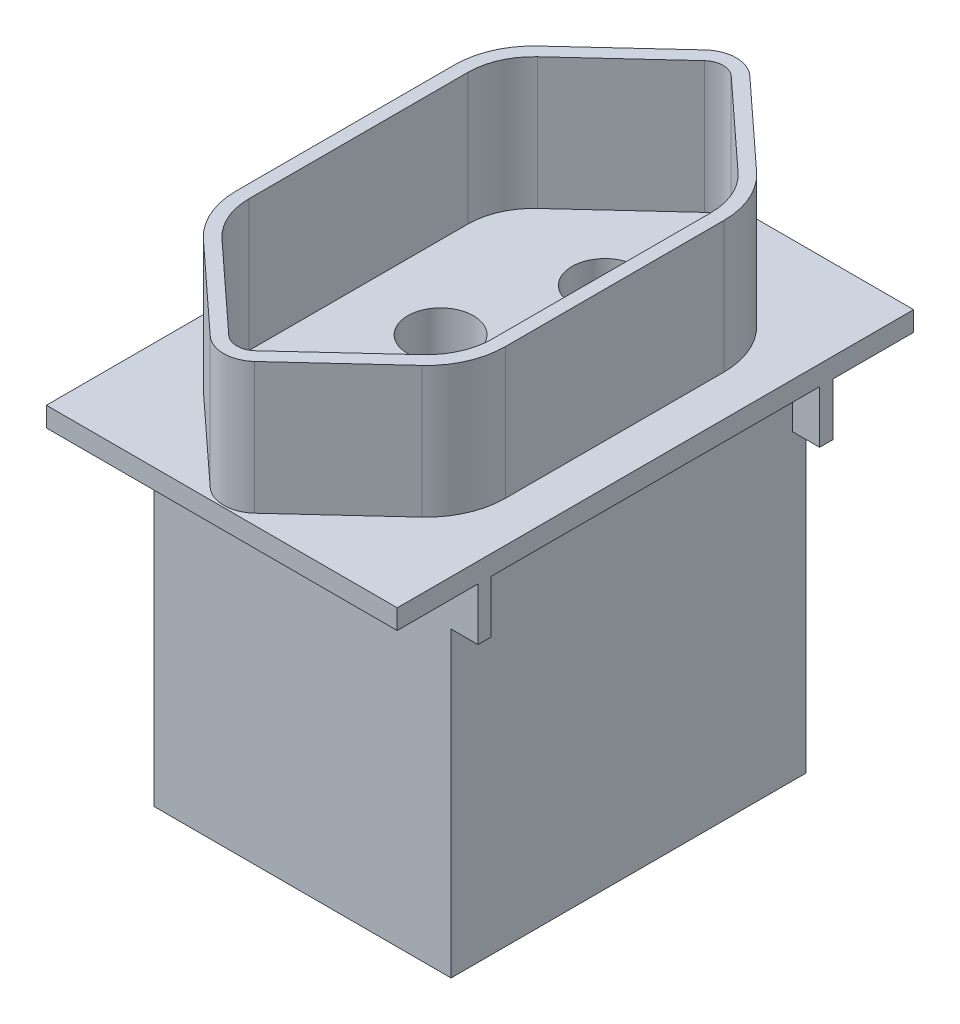
SolidWorks part; units mm, degrees
ref_plane "Plano frontal" through (0, 0, 0) normal (0, 0, 1) x (1, 0, 0)
ref_plane "Plano superior" through (0, 0, 0) normal (0, 1, 0) x (1, 0, 0)
ref_plane "Plano direito" through (0, 0, 0) normal (1, 0, 0) x (0, 0, -1)
sketch "Esboço1" plane through (0, 0, 0) normal (0, 1, 0) x (1, 0, 0)
  line L1 (-13.35, 19.65) -> (13.35, 19.65)
  line L2 (-13.35, 19.65) -> (-13.35, -19.65)
  line L3 (-13.35, -19.65) -> (13.35, -19.65)
  line L4 (13.35, 19.65) -> (13.35, -19.65)
  line L5 (-13.35, 19.65) -> (13.35, -19.65) construction
  line L6 (-13.35, -19.65) -> (13.35, 19.65) construction
  point P0 (0, 0)
  dimension "D1" = 26.7
  dimension "D2" = 39.3
extrude "Ressalto-extrusão1" add sketch "Esboço1" against normal blind 38.5
sketch "Esboço2" plane through (0, 0, 0) normal (0, 1, 0) x (1, 0, 0)
  line L0 (0, -19.04) -> (0, 19.04) construction
  line L1 (1.0166, -18.1029) -> (7.6387, -11.9991)
  line L2 (9.25, -8.3226) -> (9.25, 8.3226)
  line L3 (7.6387, 11.9991) -> (1.0166, 18.1029)
  line L4 (0, 0) -> (9.25, 0) construction
  line L5 (-1.0166, -18.1029) -> (-7.6387, -11.9991)
  line L6 (-7.6387, 11.9991) -> (-1.0166, 18.1029)
  line L7 (-9.25, -8.3226) -> (-9.25, 8.3226)
  arc A0 (9.25, 8.3226) -> (7.6387, 11.9991) centre (4.25, 8.3226) ccw
  arc A1 (7.6387, -11.9991) -> (9.25, -8.3226) centre (4.25, -8.3226) ccw
  arc A2 (-7.6387, -11.9991) -> (-9.25, -8.3226) centre (-4.25, -8.3226) cw
  arc A3 (-9.25, 8.3226) -> (-7.6387, 11.9991) centre (-4.25, 8.3226) cw
  arc A4 (1.0166, 18.1029) -> (-1.0166, 18.1029) centre (0, 17) ccw
  arc A5 (1.0166, -18.1029) -> (-1.0166, -18.1029) centre (0, -17) cw
  point P3 (0, 0)
  point P8 (6.3134, -8.4178)
  dimension "D1" = 5
  dimension "D2" = 1.5
  dimension "D3" = 37
  dimension "D4" = 28
  dimension "D5" = 18.5
extrude "Corte-extrusão1" cut sketch "Esboço2" against normal blind 10 contours A5 L1 A1 L2 A0 L3 A4 L6 A3 L7 A2 L5
sketch "Esboço4" plane through (0, 0, 0) normal (0, 1, 0) x (1, 0, 0)
  line L14 (-8.3165, -12.7344) -> (-1.6944, -18.8382)
  line L15 (1.6944, -18.8382) -> (8.3165, -12.7344)
  line L16 (10.25, -8.3226) -> (10.25, 8.3226)
  line L17 (8.3165, 12.7344) -> (1.6944, 18.8382)
  line L18 (-1.6944, 18.8382) -> (-8.3165, 12.7344)
  line L19 (-10.25, 8.3226) -> (-10.25, -8.3226)
  line L20 (1.0166, -18.1029) -> (7.6387, -11.9991)
  line L21 (9.25, -8.3226) -> (9.25, 8.3226)
  line L22 (7.6387, 11.9991) -> (1.0166, 18.1029)
  line L23 (-1.0166, 18.1029) -> (-7.6387, 11.9991)
  line L24 (-9.25, 8.3226) -> (-9.25, -8.3226)
  line L25 (-7.6387, -11.9991) -> (-1.0166, -18.1029)
  line L26 (1.0166, -18.1029) -> (7.6387, -11.9991)
  line L27 (9.25, -8.3226) -> (9.25, 8.3226)
  line L28 (7.6387, 11.9991) -> (1.0166, 18.1029)
  line L29 (-1.0166, 18.1029) -> (-7.6387, 11.9991)
  line L30 (-9.25, 8.3226) -> (-9.25, -8.3226)
  line L31 (-7.6387, -11.9991) -> (-1.0166, -18.1029)
  line L36 (13.35, -19.65) -> (13.35, 19.65)
  line L37 (13.35, 19.65) -> (-13.35, 19.65)
  line L38 (-13.35, 19.65) -> (-13.35, -19.65)
  line L39 (-13.35, -19.65) -> (13.35, -19.65)
  line L40 (13.35, -19.65) -> (13.35, 19.65)
  line L41 (13.35, 19.65) -> (-13.35, 19.65)
  line L42 (-13.35, 19.65) -> (-13.35, -19.65)
  line L43 (-13.35, -19.65) -> (13.35, -19.65)
  arc A6 (-10.25, -8.3226) -> (-8.3165, -12.7344) centre (-4.25, -8.3226) ccw
  arc A7 (-1.6944, -18.8382) -> (1.6944, -18.8382) centre (0, -17) ccw
  arc A8 (8.3165, -12.7344) -> (10.25, -8.3226) centre (4.25, -8.3226) ccw
  arc A9 (10.25, 8.3226) -> (8.3165, 12.7344) centre (4.25, 8.3226) ccw
  arc A10 (1.6944, 18.8382) -> (-1.6944, 18.8382) centre (0, 17) ccw
  arc A11 (-8.3165, 12.7344) -> (-10.25, 8.3226) centre (-4.25, 8.3226) ccw
  arc A12 (7.6387, -11.9991) -> (9.25, -8.3226) centre (4.25, -8.3226) ccw
  arc A13 (9.25, 8.3226) -> (7.6387, 11.9991) centre (4.25, 8.3226) ccw
  arc A14 (1.0166, 18.1029) -> (-1.0166, 18.1029) centre (0, 17) ccw
  arc A15 (-7.6387, 11.9991) -> (-9.25, 8.3226) centre (-4.25, 8.3226) ccw
  arc A16 (-9.25, -8.3226) -> (-7.6387, -11.9991) centre (-4.25, -8.3226) ccw
  arc A17 (-1.0166, -18.1029) -> (1.0166, -18.1029) centre (0, -17) ccw
  arc A18 (7.6387, -11.9991) -> (9.25, -8.3226) centre (4.25, -8.3226) ccw
  arc A19 (9.25, 8.3226) -> (7.6387, 11.9991) centre (4.25, 8.3226) ccw
  arc A20 (1.0166, 18.1029) -> (-1.0166, 18.1029) centre (0, 17) ccw
  arc A21 (-7.6387, 11.9991) -> (-9.25, 8.3226) centre (-4.25, 8.3226) ccw
  arc A22 (-9.25, -8.3226) -> (-7.6387, -11.9991) centre (-4.25, -8.3226) ccw
  arc A23 (-1.0166, -18.1029) -> (1.0166, -18.1029) centre (0, -17) ccw
  line M41 (13.35, -19.65) -> (13.35, 19.65)
  line M42 (13.35, 19.65) -> (-13.35, 19.65)
  line M43 (-13.35, 19.65) -> (-13.35, -19.65)
  line M44 (-13.35, -19.65) -> (13.35, -19.65)
  dimension "D1" = 0
  dimension "D2" = 1
  dimension "D3" = 0
extrude "Corte-extrusão2" cut sketch "Esboço4" against normal blind 10 contours A11 L18 A10 L17 A9 L16 A8 L15 A7 L14 A6 L19 M44 M41 M42 M43
sketch "Esboço5" plane through (0, -38.5, 0) normal (0, -1, 0) x (1, 0, 0)
  line L1 (11.3, -13.5) -> (-11.3, -13.5)
  line L2 (11.3, -13.5) -> (11.3, 13.5)
  line L3 (11.3, 13.5) -> (-11.3, 13.5)
  line L4 (-11.3, -13.5) -> (-11.3, 13.5)
  line L5 (11.3, -13.5) -> (-11.3, 13.5) construction
  line L6 (11.3, 13.5) -> (-11.3, -13.5) construction
  line L10 (13.35, -19.65) -> (13.35, 19.65)
  line L11 (13.35, 19.65) -> (-13.35, 19.65)
  line L12 (-13.35, 19.65) -> (-13.35, -19.65)
  line L13 (-13.35, -19.65) -> (13.35, -19.65)
  line L14 (13.35, -19.65) -> (13.35, 19.65)
  line L15 (13.35, 19.65) -> (-13.35, 19.65)
  line L16 (-13.35, 19.65) -> (-13.35, -19.65)
  line L17 (-13.35, -19.65) -> (13.35, -19.65)
  point P0 (0, 0)
  line M3 (13.35, -19.65) -> (13.35, 19.65)
  line M4 (13.35, 19.65) -> (-13.35, 19.65)
  line M5 (-13.35, 19.65) -> (-13.35, -19.65)
  line M6 (-13.35, -19.65) -> (13.35, -19.65)
  dimension "D1" = 27
  dimension "D2" = 22.6
  dimension "D3" = 0
extrude "Corte-extrusão4" cut sketch "Esboço5" against normal blind 27 contours L1 L4 L3 L2 M6 M3 M4 M5 | L14 L15 L16 L17
sketch "Esboço6" plane through (0, -10, 0) normal (0, 1, 0) x (1, 0, 0)
  line L0 (0, -9.5) -> (0, 9.5) construction
  line L1 (0, 0) -> (-3, 0) construction
  circle A0 centre (0, -9.5) radius 2.5
  circle A1 centre (0, 9.5) radius 2.5
  circle A2 centre (-3, 0) radius 2.5
  point P3 (0, 0)
  dimension "D1" = 5
  dimension "D2" = 19
  dimension "D3" = 3
extrude "Corte-extrusão5" cut sketch "Esboço6" against normal blind 5
sketch "Esboço7" plane through (0, -11.5, 0) normal (0, -1, 0) x (1, 0, 0)
  line L0 (13.35, -19.65) -> (13.35, 19.65) construction
  line L1 (11.3, 13.5) -> (13.35, 13.5)
  line L2 (11.3, 13.5) -> (11.3, 12.5)
  line L3 (11.3, 12.5) -> (13.35, 12.5)
  line L4 (13.35, 13.5) -> (13.35, 12.5)
  line L5 (0, 0) -> (0, 13.5) construction
  line L6 (11.3, 13.5) -> (-11.3, 13.5) construction
  line L7 (0, 0) -> (11.3, 0) construction
  line L8 (11.3, -13.5) -> (11.3, 13.5) construction
  line L9 (-13.35, 13.5) -> (-13.35, 12.5)
  line L10 (-11.3, 12.5) -> (-13.35, 12.5)
  line L11 (-11.3, 13.5) -> (-11.3, 12.5)
  line L12 (-11.3, 13.5) -> (-13.35, 13.5)
  line L13 (-11.3, -13.5) -> (-13.35, -13.5)
  line L14 (-11.3, -13.5) -> (-11.3, -12.5)
  line L15 (-11.3, -12.5) -> (-13.35, -12.5)
  line L16 (-13.35, -13.5) -> (-13.35, -12.5)
  line L17 (13.35, -13.5) -> (13.35, -12.5)
  line L18 (11.3, -12.5) -> (13.35, -12.5)
  line L19 (11.3, -13.5) -> (11.3, -12.5)
  line L20 (11.3, -13.5) -> (13.35, -13.5)
  dimension "D1" = 1
extrude "Ressalto-extrusão2" add sketch "Esboço7" along normal blind 4
